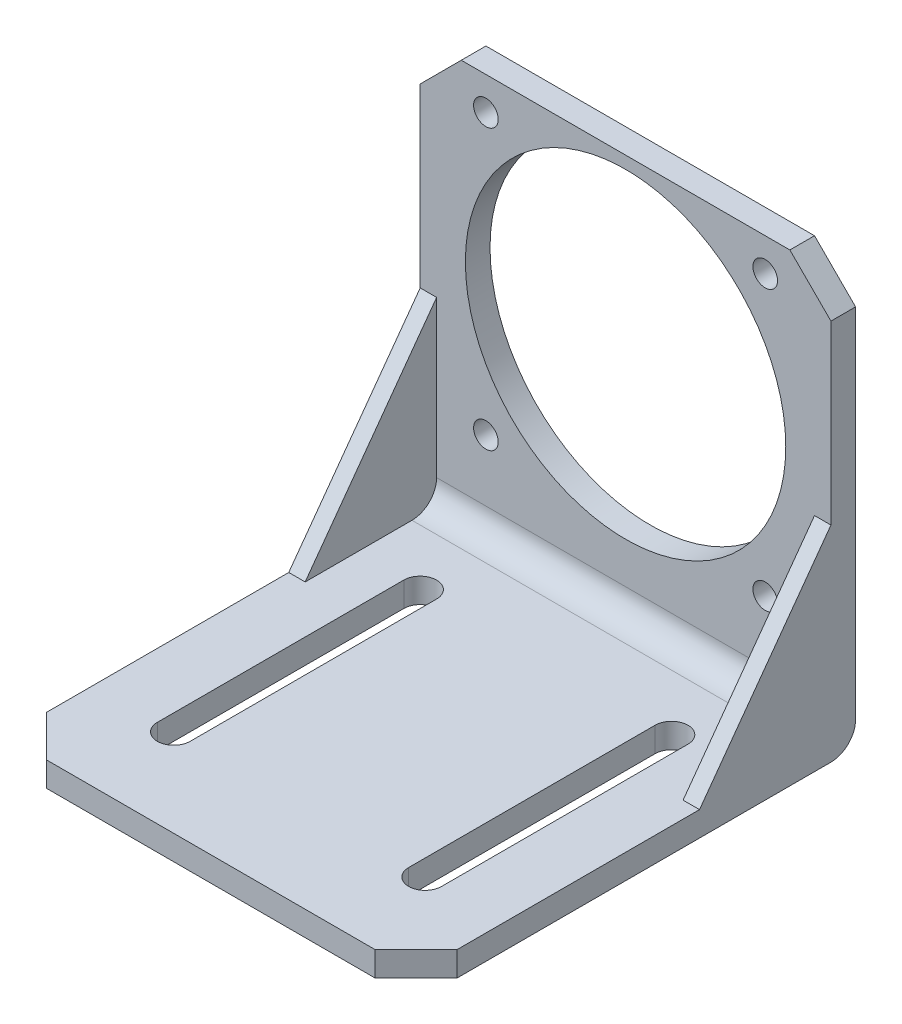
SolidWorks part; units mm, degrees
ref_plane "前视基准面" through (0, 0, 0) normal (0, 0, 1) x (1, 0, 0)
ref_plane "上视基准面" through (0, 0, 0) normal (0, 1, 0) x (1, 0, 0)
ref_plane "右视基准面" through (0, 0, 0) normal (1, 0, 0) x (0, 0, -1)
sketch "草图1" plane through (0, 0, 0) normal (0, 0, 1) x (1, 0, 0)
  line L1 (-25, 25.75) -> (25, 25.75)
  line L2 (-25, 25.75) -> (-25, -25.75)
  line L3 (-25, -25.75) -> (25, -25.75)
  line L4 (25, 25.75) -> (25, -25.75)
  line L5 (-25, 25.75) -> (25, -25.75) construction
  line L6 (-25, -25.75) -> (25, 25.75) construction
  line L7 (-20, 25.75) -> (-25, 20.75)
  line L8 (20, 25.75) -> (25, 20.75)
  circle A0 centre (0, 4.75) radius 19.5
  circle A1 centre (-17, 21.75) radius 1.5
  circle A2 centre (17, 21.75) radius 1.5
  circle A3 centre (17, -12.25) radius 1.5
  circle A4 centre (-17, -12.25) radius 1.5
  point P0 (0, 0)
  point P23 (0, 4.75)
  dimension "D6" = 39
  dimension "D11" = 3
  dimension "D1" = 51.5
  dimension "D2" = 50
  dimension "D3" = 17
  dimension "D4" = 25
  dimension "D5" = 21
  dimension "D7" = 5
  dimension "D8" = 5
  dimension "D9" = 5
  dimension "D10" = 5
  dimension "D12" = 17
  dimension "D13" = 4
extrude "凸台-拉伸1" add sketch "草图1" along normal blind 3
sketch "草图2" plane through (0, -25.75, 0) normal (0, -1, 0) x (1, 0, 0)
  line L0 (-25, 0) -> (25, 0)
  line L1 (-25, 0) -> (-25, 53.5)
  line L2 (25, 0) -> (25, 53.5)
  line L3 (-25, 53.5) -> (25, 53.5)
  line L4 (25, 48.5) -> (20, 53.5)
  line L5 (20, 53.5) -> (-20, 53.5)
  line L6 (-20, 53.5) -> (-25, 48.5)
  line L7 (-15.2, 12.8) -> (-15.2, 42.8) construction
  line L8 (-17.2, 12.8) -> (-17.2, 42.8)
  line L9 (-13.2, 12.8) -> (-13.2, 42.8)
  line L10 (15.4, 12.8) -> (15.4, 42.8) construction
  line L11 (13.4, 12.8) -> (13.4, 42.8)
  line L12 (17.4, 12.8) -> (17.4, 42.8)
  arc A0 (-17.2, 12.8) -> (-13.2, 12.8) centre (-15.2, 12.8) ccw
  arc A1 (-13.2, 42.8) -> (-17.2, 42.8) centre (-15.2, 42.8) ccw
  arc A2 (13.4, 12.8) -> (17.4, 12.8) centre (15.4, 12.8) ccw
  arc A3 (17.4, 42.8) -> (13.4, 42.8) centre (15.4, 42.8) ccw
  point P12 (-15.2, 27.8)
  point P21 (15.4, 27.8)
  line M4 (25, 3) -> (-25, 3)
  dimension "D8" = 2
  dimension "D9" = 10.7
  dimension "D1" = 53.5
  dimension "D2" = 5
  dimension "D3" = 5
  dimension "D4" = 5
  dimension "D5" = 5
  dimension "D6" = 7.8
  dimension "D7" = 30
  dimension "D11" = 10.7
  dimension "D12" = 7.6
  dimension "D10" = 2
extrude "凸台-拉伸3" add sketch "草图2" against normal blind 3 contours L3 L6 L1 L2 L4 M4
sketch "草图3" plane through (25, 0, 0) normal (1, 0, 0) x (0, 0, -1)
  line L0 (-3, -0.75) -> (-3, -22.75)
  line L2 (-3, 20.75) -> (-3, -22.75) construction
  line L4 (-3, -22.75) -> (-19, -22.75)
  line L5 (-3, -22.75) -> (-48.5, -22.75) construction
  line L6 (-19, -22.75) -> (-3, -0.75)
  dimension "D1" = 22
  dimension "D2" = 16
extrude "凸台-拉伸4" add sketch "草图3" against normal blind 2
mirror "镜向1" about plane through (0, 0, 0) normal (1, 0, 0) of "凸台-拉伸4"
fillet "圆角2" radius 3 2 edges at (0, -25.75, 0)
